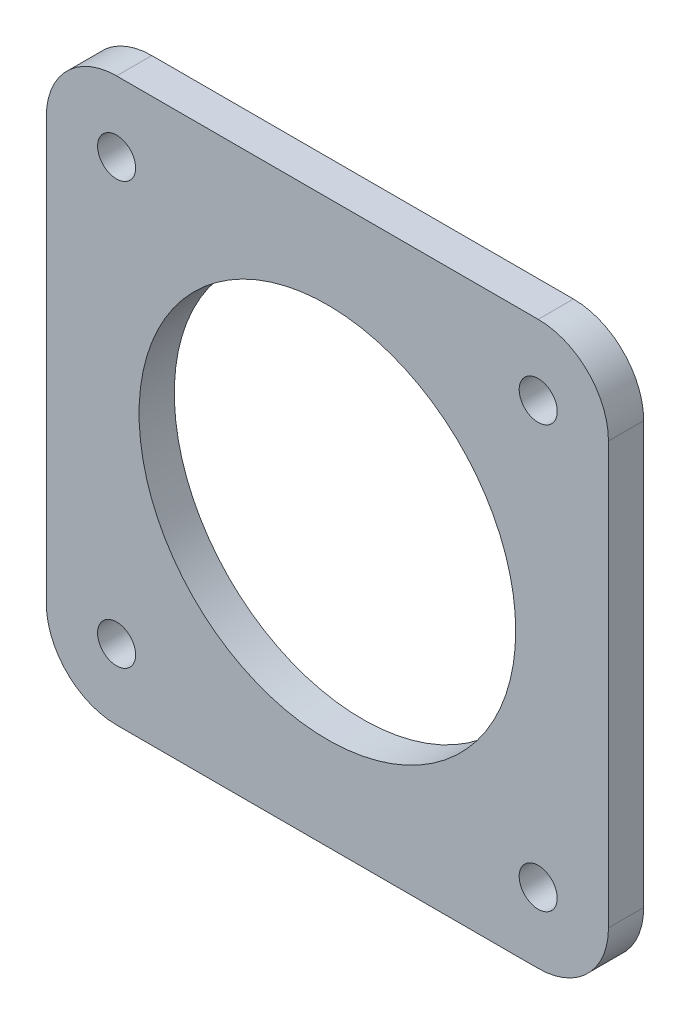
SolidWorks part; units mm, degrees
ref_plane "front" through (0, 0, 0) normal (0, 0, 1) x (1, 0, 0)
ref_plane "top" through (0, 0, 0) normal (0, 1, 0) x (1, 0, 0)
ref_plane "right" through (0, 0, 0) normal (1, 0, 0) x (0, 0, -1)
sketch "Sketch1" plane through (0, 0, 0) normal (0, 0, 1) x (1, 0, 0)
  line L0 (0, 0) -> (0, 18.2924) construction
  line L1 (-28.575, 38.1) -> (28.575, 38.1)
  line L2 (-38.1, 28.575) -> (-38.1, -28.575)
  line L3 (-28.575, -38.1) -> (28.575, -38.1)
  line L4 (38.1, 28.575) -> (38.1, -28.575)
  line L5 (0, 0) -> (15.8534, 0) construction
  circle A0 centre (0, 0) radius 25.527
  circle A1 centre (-28.575, 28.575) radius 2.5781
  circle A2 centre (28.575, 28.575) radius 2.5781
  circle A3 centre (-28.575, -28.575) radius 2.5781
  circle A4 centre (28.575, -28.575) radius 2.5781
  arc A5 (28.575, 38.1) -> (38.1, 28.575) centre (28.575, 28.575) cw
  arc A6 (-28.575, 38.1) -> (-38.1, 28.575) centre (-28.575, 28.575) ccw
  arc A7 (-38.1, -28.575) -> (-28.575, -38.1) centre (-28.575, -28.575) ccw
  arc A8 (28.575, -38.1) -> (38.1, -28.575) centre (28.575, -28.575) ccw
  point P4 (0, 38.1)
  point P5 (38.1, 0)
  point P21 (38.1, 38.1)
  point P24 (-38.1, 38.1)
  point P29 (38.1, -38.1)
  dimension "D1" = 51.054
  dimension "D6" = 5.1562
  dimension "D7" = 9.525
  dimension "D2" = 57.15
  dimension "D3" = 57.15
  dimension "D4" = 76.2
  dimension "D5" = 76.2
extrude "Extrude1" add sketch "Sketch1" against normal blind 4.7752
